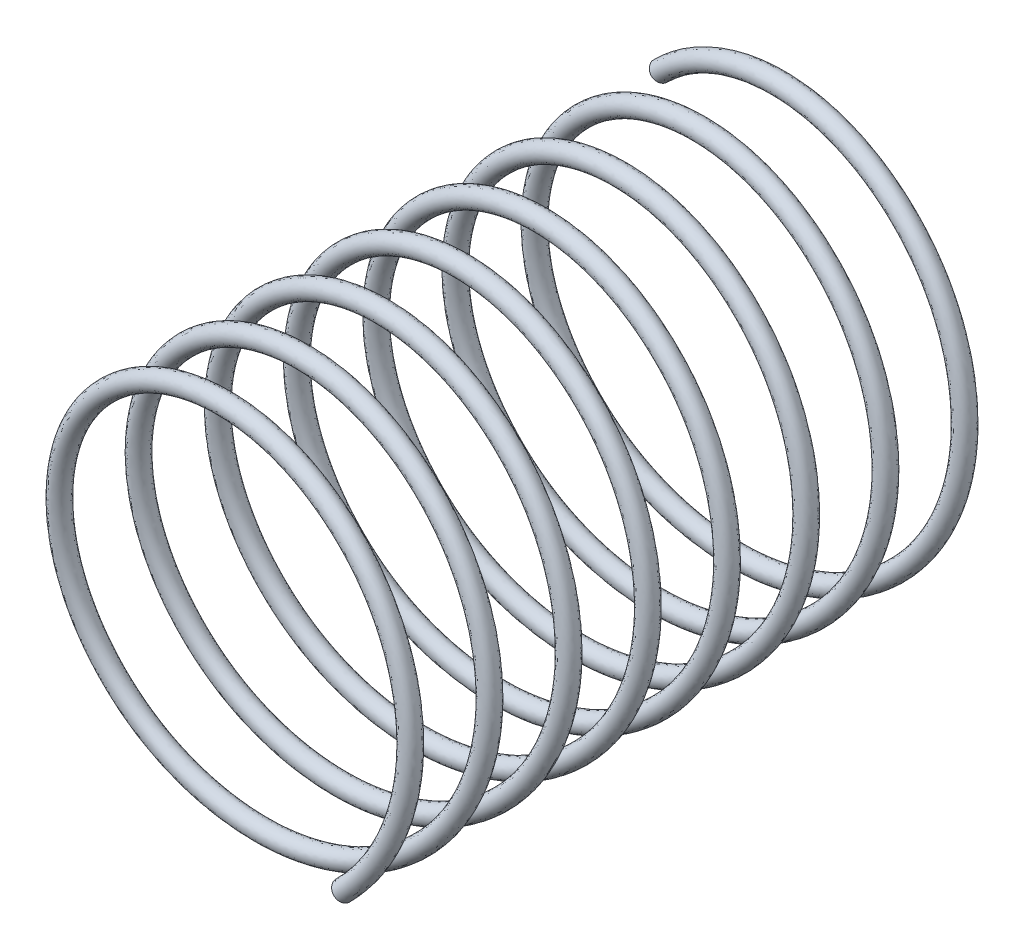
SolidWorks part; units mm, degrees
ref_plane "Front" through (0, 0, 0) normal (0, 0, 1) x (1, 0, 0)
ref_plane "Top" through (0, 0, 0) normal (0, 1, 0) x (1, 0, 0)
ref_plane "Right" through (0, 0, 0) normal (1, 0, 0) x (0, 0, -1)
sketch "Sketch1" plane through (0, 0, 0) normal (0, 0, 1) x (1, 0, 0)
  circle A0 centre (0, 0) radius 1.9812 construction
  circle A1 centre (0, 0) radius 2.1844 construction
  circle A2 centre (0, 0) radius 2.0828
  dimension "D1" = 3.9624
  dimension "D2" = 4.3688
  dimension "D3" = 4.1656
curve "Helix/Spiral1" pitch 0.8467 height 6.35 turns 7.5
ref_plane "Plane1" through (1.4728, -1.4728, 6.35) normal (-0.7056, -0.7056, 0.0646) x (0.0457, 0.0457, 0.9979)
sweep "Sweep1" add path "Helix/Spiral1" circular profile diameter 0.2032 parameters "D3"=0.2032
ref_plane "Plane2" through (0, 0, 0.0254) normal (0, 0, 1) x (1, 0, 0)
sketch "Sketch11" plane through (0, 0, 0.0254) normal (0, 0, 1) x (1, 0, 0)
  circle A0 centre (0, 0) radius 2.9961
extrude "Cut-Extrude1" cut sketch "Sketch11" against normal blind 2.54
sketch "Sketch12" plane through (0, 0, 0.0254) normal (0, 0, 1) x (1, 0, 0)
  circle A0 centre (0, 0) radius 2.1812
